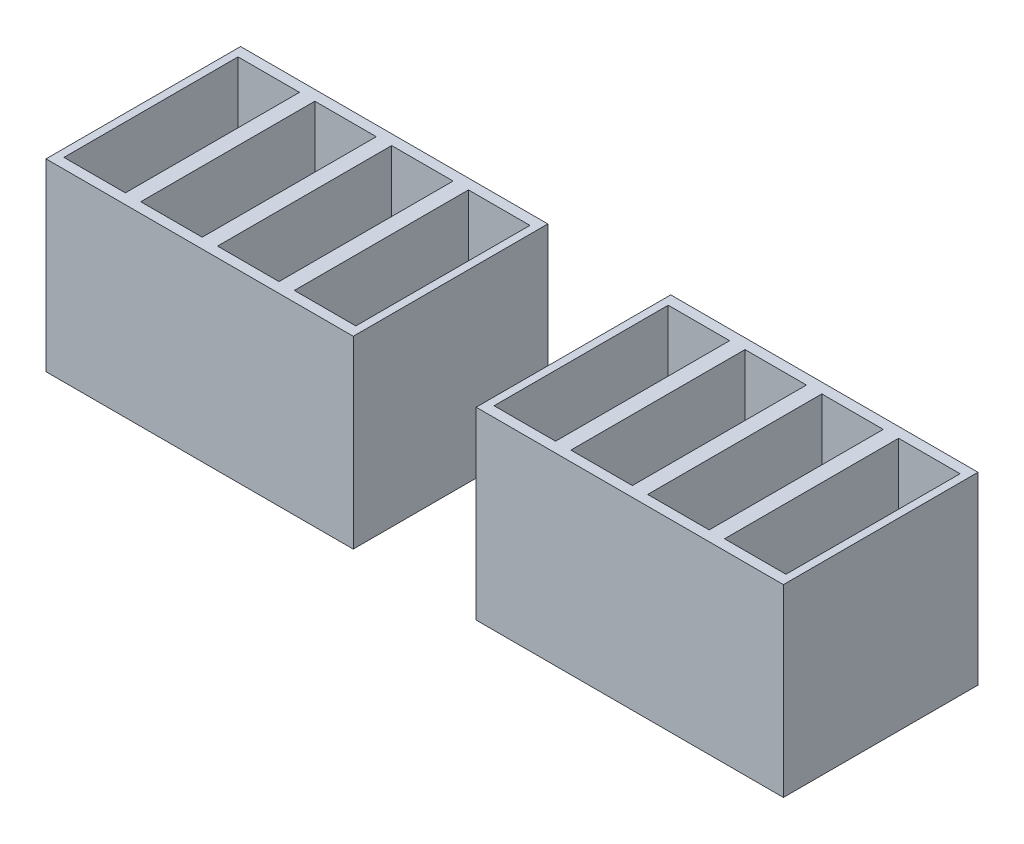
SolidWorks part; units mm, degrees
ref_plane "Front Plane" through (0, 0, 0) normal (0, 0, 1) x (1, 0, 0)
ref_plane "Top Plane" through (0, 0, 0) normal (0, 1, 0) x (1, 0, 0)
ref_plane "Right Plane" through (0, 0, 0) normal (1, 0, 0) x (0, 0, -1)
sketch "Sketch1" plane through (0, 0, 0) normal (0, 1, 0) x (1, 0, 0)
  line L0 (-1066.8, 482.6) -> (-1066.8, -482.6) construction
  line L1 (-1828.8, 482.6) -> (-304.8, 482.6)
  line L2 (-1828.8, 482.6) -> (-1828.8, -482.6)
  line L3 (-1828.8, -482.6) -> (-304.8, -482.6)
  line L4 (-304.8, 482.6) -> (-304.8, -482.6)
  line L5 (-1790.7, 0) -> (-1485.9, 0) construction
  line L6 (-1790.7, 431.8) -> (-1485.9, 431.8)
  line L7 (-1790.7, 431.8) -> (-1790.7, -431.8)
  line L8 (-1790.7, -431.8) -> (-1485.9, -431.8)
  line L9 (-1485.9, 431.8) -> (-1485.9, -431.8)
  line L10 (-1409.7, 431.8) -> (-1409.7, -431.8)
  line L11 (-1409.7, 431.8) -> (-1104.9, 431.8)
  line L12 (-1104.9, 431.8) -> (-1104.9, -431.8)
  line L13 (-1409.7, -431.8) -> (-1104.9, -431.8)
  line L14 (-1028.7, 431.8) -> (-1028.7, -431.8)
  line L15 (-1028.7, 431.8) -> (-723.9, 431.8)
  line L16 (-723.9, 431.8) -> (-723.9, -431.8)
  line L17 (-1028.7, -431.8) -> (-723.9, -431.8)
  line L18 (-647.7, 431.8) -> (-647.7, -431.8)
  line L19 (-647.7, 431.8) -> (-342.9, 431.8)
  line L20 (-342.9, 431.8) -> (-342.9, -431.8)
  line L21 (-647.7, -431.8) -> (-342.9, -431.8)
  line L22 (0, 1277.468) -> (0, -1043.2112) construction
  line L23 (647.7, 431.8) -> (342.9, 431.8)
  line L24 (342.9, 431.8) -> (342.9, -431.8)
  line L25 (647.7, -431.8) -> (342.9, -431.8)
  line L26 (647.7, 431.8) -> (647.7, -431.8)
  line L27 (1028.7, 431.8) -> (723.9, 431.8)
  line L28 (723.9, 431.8) -> (723.9, -431.8)
  line L29 (1028.7, -431.8) -> (723.9, -431.8)
  line L30 (1028.7, 431.8) -> (1028.7, -431.8)
  line L31 (1409.7, 431.8) -> (1104.9, 431.8)
  line L32 (1104.9, 431.8) -> (1104.9, -431.8)
  line L33 (1409.7, -431.8) -> (1104.9, -431.8)
  line L34 (1409.7, 431.8) -> (1409.7, -431.8)
  line L35 (1790.7, -431.8) -> (1485.9, -431.8)
  line L36 (1485.9, 431.8) -> (1485.9, -431.8)
  line L37 (1790.7, 431.8) -> (1485.9, 431.8)
  line L38 (1790.7, 431.8) -> (1790.7, -431.8)
  line L39 (1828.8, -482.6) -> (304.8, -482.6)
  line L40 (304.8, 482.6) -> (304.8, -482.6)
  line L41 (1828.8, 482.6) -> (304.8, 482.6)
  line L42 (1828.8, 482.6) -> (1828.8, -482.6)
  point P6 (-1066.8, 0)
  point P14 (-1638.3, 0)
  dimension "D1" = 1524
  dimension "D2" = 965.2
  dimension "D3" = 304.8
  dimension "D4" = 863.6
  dimension "D5" = 38.1
  dimension "D6" = 4
  dimension "D7" = 304.8
extrude "Boss-Extrude2" add sketch "Sketch1" along normal blind 914.4
